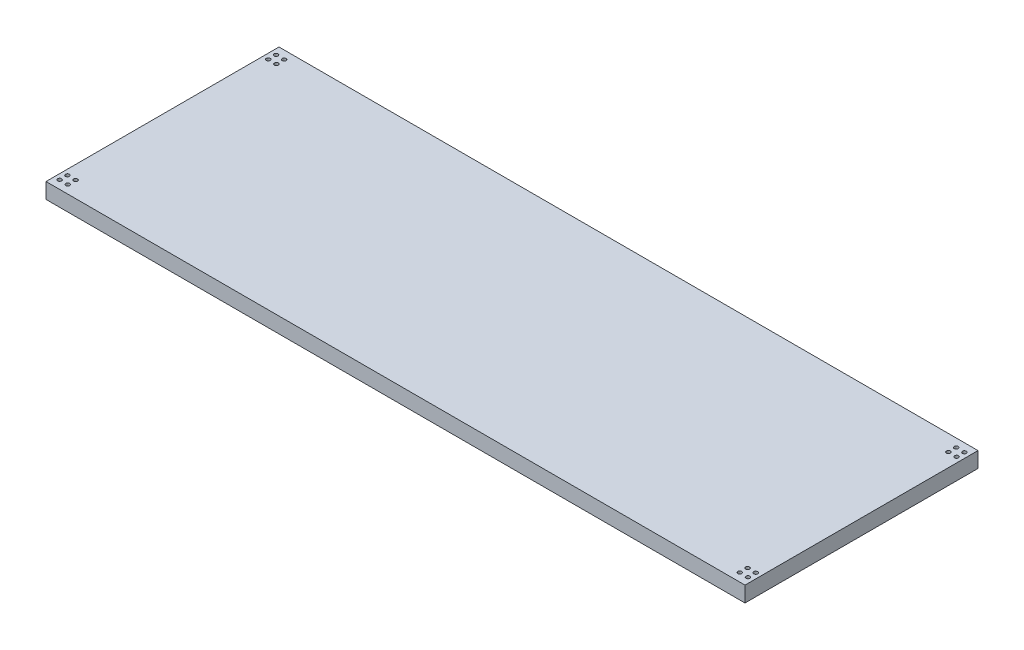
SolidWorks part; units mm, degrees
ref_plane "Front Plane" through (0, 0, 0) normal (0, 0, 1) x (1, 0, 0)
ref_plane "Top Plane" through (0, 0, 0) normal (0, 1, 0) x (1, 0, 0)
ref_plane "Right Plane" through (0, 0, 0) normal (1, 0, 0) x (0, 0, -1)
sketch "Sketch2" plane through (0, 0, 0) normal (0, 1, 0) x (1, 0, 0)
  line L0 (0, 300) -> (0, -300) construction
  line L1 (-900, 300) -> (900, 300)
  line L2 (-900, 300) -> (-900, -300)
  line L3 (-900, -300) -> (900, -300)
  line L4 (900, 300) -> (900, -300)
  line L5 (-900, 0) -> (900, 0) construction
  circle A0 centre (-886.2732, -278.618) radius 5
  circle A1 centre (-865.2447, -278.618) radius 5
  circle A2 centre (-865.2447, -258.618) radius 5
  circle A3 centre (-886.2732, -258.618) radius 5
  circle A4 centre (886.2732, -278.618) radius 5
  circle A5 centre (886.2732, -258.618) radius 5
  circle A6 centre (865.2447, -258.618) radius 5
  circle A7 centre (865.2447, -278.618) radius 5
  circle A8 centre (865.2447, 278.618) radius 5
  circle A9 centre (886.2732, 278.618) radius 5
  circle A10 centre (886.2732, 258.618) radius 5
  circle A11 centre (865.2447, 258.618) radius 5
  circle A12 centre (-886.2732, 278.618) radius 5
  circle A13 centre (-865.2447, 278.618) radius 5
  circle A14 centre (-865.2447, 258.618) radius 5
  circle A15 centre (-886.2732, 258.618) radius 5
  point P0 (0, 0)
  dimension "D3" = 10
  dimension "D1" = 1800
  dimension "D2" = 600
  dimension "D4" = 2
  dimension "D5" = 2
extrude "Boss-Extrude1" add sketch "Sketch2" along normal blind 40
